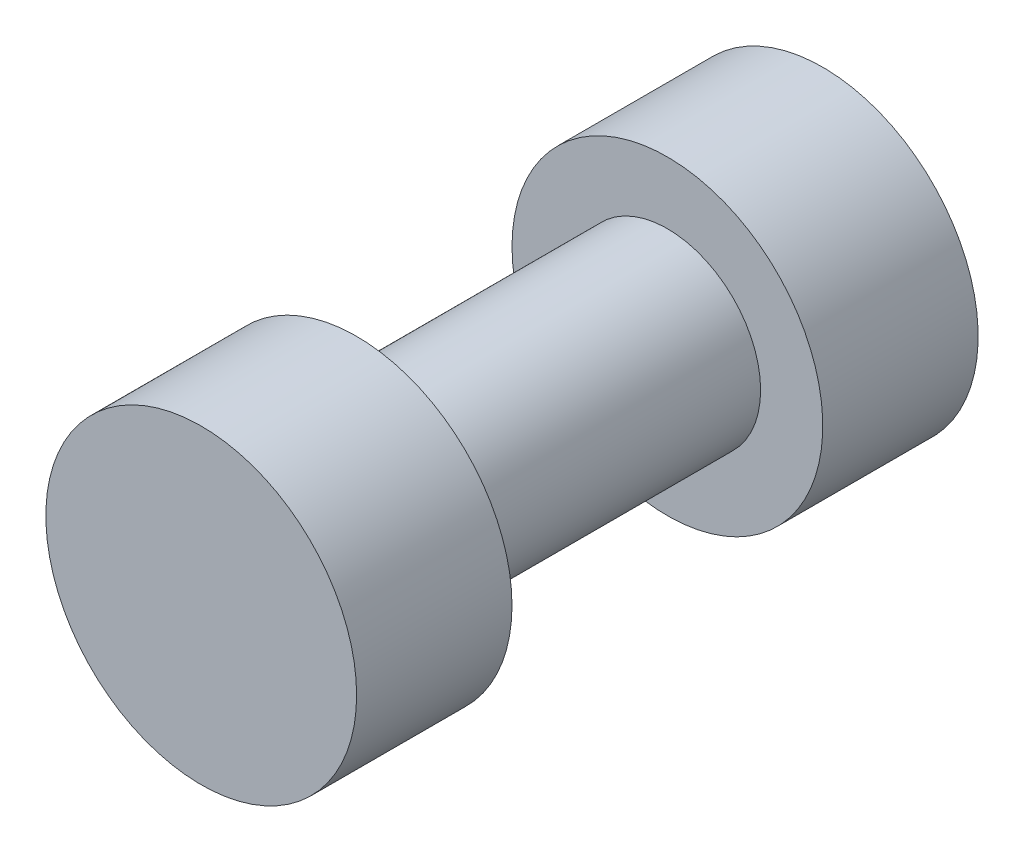
SolidWorks part; units mm, degrees
material "Acier allié inoxydable"
ref_plane "Plan de face" through (0, 0, 0) normal (0, 0, 1) x (1, 0, 0)
ref_plane "Plan de dessus" through (0, 0, 0) normal (0, 1, 0) x (1, 0, 0)
ref_plane "Plan de droite" through (0, 0, 0) normal (1, 0, 0) x (0, 0, -1)
sketch "Esquisse1" plane through (0, 0, 0) normal (0, 0, 1) x (1, 0, 0)
  circle A0 centre (0, 0) radius 3
  dimension "D1" = 6
extrude "Boss.-Extru.1" add sketch "Esquisse1" along normal blind 10 contours A0
sketch "Esquisse2" plane through (0, 0, 10) normal (0, 0, 1) x (1, 0, 0)
  circle A0 centre (0, 0) radius 5
  dimension "D1" = 10
extrude "Boss.-Extru.3" add sketch "Esquisse2" along normal blind 5 contours A0
sketch "Esquisse3" plane through (0, 0, 0) normal (0, 0, -1) x (-1, 0, 0)
  circle A0 centre (0, 0) radius 5
  dimension "D1" = 10
extrude "Boss.-Extru.4" add sketch "Esquisse3" along normal blind 5 contours A0
